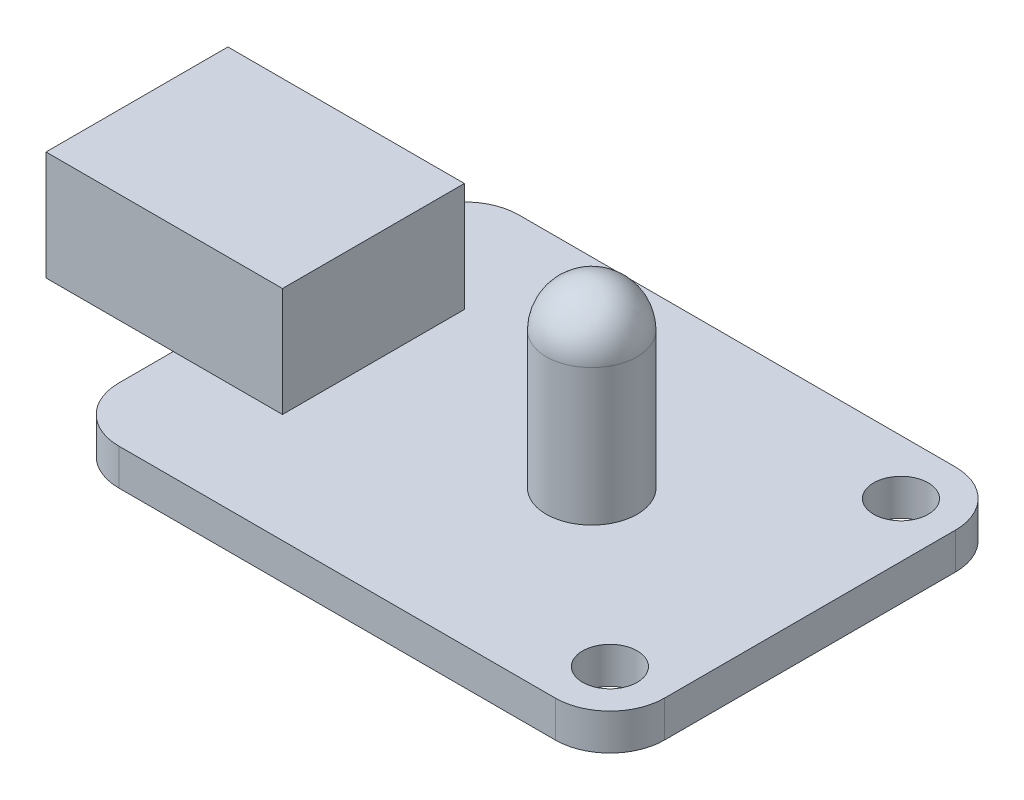
SolidWorks part; units mm, degrees
ref_plane "Front Plane" through (0, 0, 0) normal (0, 0, 1) x (1, 0, 0)
ref_plane "Top Plane" through (0, 0, 0) normal (0, 1, 0) x (1, 0, 0)
ref_plane "Right Plane" through (0, 0, 0) normal (1, 0, 0) x (0, 0, -1)
sketch "Sketch1" plane through (0, 0, 0) normal (0, 1, 0) x (1, 0, 0)
  line L1 (-12, 11) -> (12, 11)
  line L2 (-15, 8) -> (-15, -8)
  line L3 (-12, -11) -> (12, -11)
  line L4 (15, 8) -> (15, -8)
  line L5 (-15, 11) -> (15, -11) construction
  line L6 (-15, -11) -> (15, 11) construction
  circle A0 centre (12, 8) radius 1.5
  circle A1 centre (12, -8) radius 1.5
  arc A2 (15, 8) -> (12, 11) centre (12, 8) ccw
  arc A3 (-15, 8) -> (-12, 11) centre (-12, 8) cw
  arc A4 (-15, -8) -> (-12, -11) centre (-12, -8) ccw
  arc A5 (15, -8) -> (12, -11) centre (12, -8) cw
  point P0 (0, 0)
  dimension "D3" = 3
  dimension "D4" = 3
  dimension "D9" = 3
  dimension "D10" = 3
  dimension "D11" = 3
  dimension "D12" = 3
  dimension "D1" = 30
  dimension "D2" = 22
  dimension "D5" = 3
  dimension "D6" = 3
  dimension "D7" = 3
  dimension "D8" = 3
extrude "Boss-Extrude1" add sketch "Sketch1" along normal blind 2
sketch "Sketch2" plane through (0, 2, 0) normal (0, 1, 0) x (1, 0, 0)
  line L0 (-15, 8) -> (-15, -8) construction
  line L1 (-22, 5) -> (-9, 5)
  line L2 (-22, 5) -> (-22, -5)
  line L3 (-22, -5) -> (-9, -5)
  line L4 (-9, 5) -> (-9, -5)
  line L5 (-22, 5) -> (-9, -5) construction
  line L6 (-22, -5) -> (-9, 5) construction
  point P0 (-15.5, 0)
  dimension "D1" = 10
  dimension "D2" = 13
  dimension "D3" = 6
extrude "Boss-Extrude2" add sketch "Sketch2" along normal blind 6
sketch "Sketch3" plane through (0, 2, 0) normal (0, 1, 0) x (1, 0, 0)
  line L0 (15, -8) -> (15, 8) construction
  circle A0 centre (3, 0) radius 2.5
  point P3 (0, 0)
  point P4 (3.0868, 0.2352)
  dimension "D1" = 5
  dimension "D2" = 12
extrude "Boss-Extrude3" add sketch "Sketch3" along normal blind 10
fillet "Fillet1" radius 2.5 1 edges at (3, 12, 2.5)
